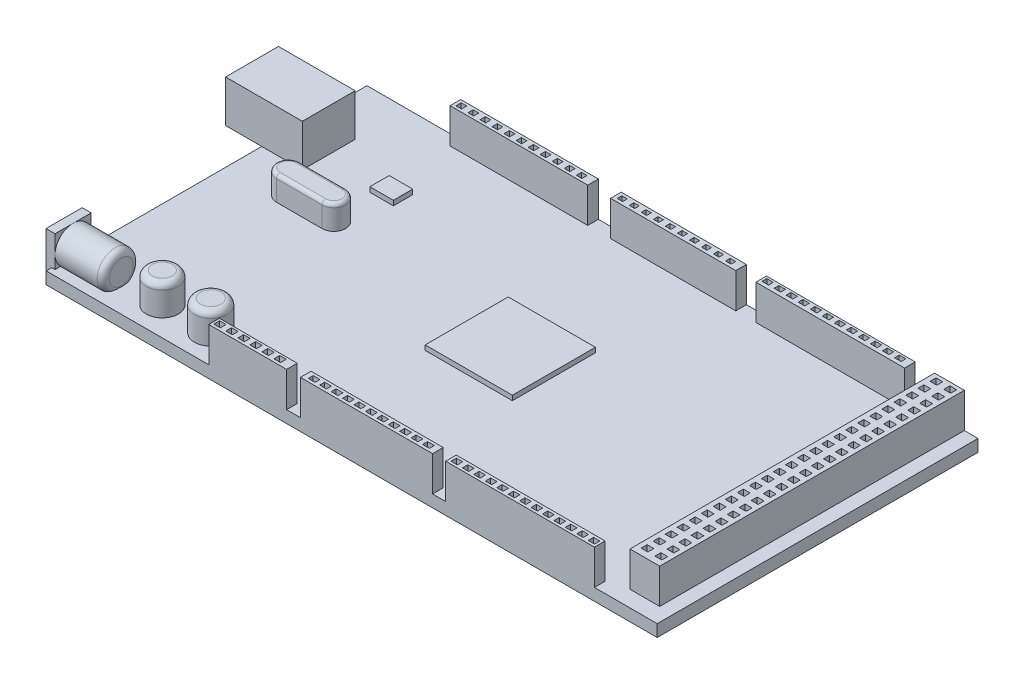
SolidWorks part; units mm, degrees
ref_plane "Front Plane" through (0, 0, 0) normal (0, 0, 1) x (1, 0, 0)
ref_plane "Top Plane" through (0, 0, 0) normal (0, 1, 0) x (1, 0, 0)
ref_plane "Right Plane" through (0, 0, 0) normal (1, 0, 0) x (0, 0, -1)
other "Center of Mass"
sketch "Sketch1" plane through (0, 0, 0) normal (0, 1, 0) x (1, 0, 0)
  line L1 (-53.5463, 29.6807) -> (47.9737, 29.6807)
  line L2 (-53.5463, 29.6807) -> (-53.5463, -23.6193)
  line L3 (-53.5463, -23.6193) -> (47.9737, -23.6193)
  line L4 (47.9737, 29.6807) -> (47.9737, -23.6193)
  dimension "D1" = 101.52
  dimension "D2" = 53.3
extrude "Boss-Extrude1" add sketch "Sketch1" along normal blind 2
sketch "Sketch2" plane through (0, 2, 0) normal (0, 1, 0) x (1, 0, 0)
  line L0 (-53.5463, 29.6807) -> (-53.5463, -23.6193) construction
  line L1 (-53.5463, 20.9714) -> (-46.798, 20.9714)
  line L2 (-53.5463, 20.9714) -> (-53.5463, 12.1907)
  line L3 (-53.5463, 12.1907) -> (-46.798, 12.1907)
  line L4 (-46.798, 20.9714) -> (-46.798, 12.1907)
extrude "Boss-Extrude2" add sketch "Sketch2" along normal blind 7
sketch "Sketch3" plane through (-53.5463, 0, 0) normal (-1, 0, 0) x (0, 0, 1)
  line L1 (-20.9714, 9) -> (-12.1907, 9)
  line L2 (-20.9714, 9) -> (-20.9714, 2)
  line L3 (-20.9714, 2) -> (-12.1907, 2)
  line L4 (-12.1907, 9) -> (-12.1907, 2)
extrude "Boss-Extrude3" add sketch "Sketch3" along normal blind 6
sketch "Sketch4" plane through (-59.5463, 0, 0) normal (-1, 0, 0) x (0, 0, 1)
  line L0 (-16.581, 9) -> (-16.581, 2) construction
  line L1 (-12.1907, 9) -> (-20.9714, 9) construction
  line L2 (-20.9714, 2) -> (-12.1907, 2) construction
  line L3 (-14.3094, 7.9433) -> (-18.8527, 7.9433)
  line L4 (-18.8527, 7.9433) -> (-20.4463, 6.3497)
  line L5 (-20.4463, 6.3497) -> (-20.4463, 2.9918)
  line L6 (-20.4463, 2.9918) -> (-12.7158, 2.9918)
  line L7 (-12.7158, 6.3497) -> (-12.7158, 2.9918)
  line L8 (-14.3094, 7.9433) -> (-12.7158, 6.3497)
  line L10 (-18.8527, 5.6667) -> (-14.3094, 5.6667)
  line L11 (-18.8527, 5.6667) -> (-18.8527, 4.6423)
  line L12 (-18.8527, 4.6423) -> (-14.3094, 4.6423)
  line L13 (-14.3094, 5.6667) -> (-14.3094, 4.6423)
  point P12 (-16.581, 2.9918)
  point P14 (-16.581, 7.9433)
extrude "Cut-Extrude1" cut sketch "Sketch4" against normal blind 10
ref_plane "Plane1" through (-45, 0, 0) normal (1, 0, 0) x (0, 0, -1)
sketch "Sketch5" plane through (-45, 0, 0) normal (1, 0, 0) x (0, 0, -1)
  circle A0 centre (-19.695, 4.1557) radius 3
  dimension "D1" = 6
extrude "Boss-Extrude4" add sketch "Sketch5" against normal blind 8 separate body
fillet "Fillet1" radius 1 1 edges at (-45, 4.1557, 16.695)
sketch "Sketch6" plane through (-53, 0, 0) normal (-1, 0, 0) x (0, 0, 1)
  line L1 (16.695, 1.1557) -> (22.695, 1.1557)
  line L2 (16.695, 1.1557) -> (16.695, 7.1557)
  line L3 (16.695, 7.1557) -> (22.695, 7.1557)
  line L4 (22.695, 1.1557) -> (22.695, 7.1557)
  line L5 (16.695, 1.1557) -> (22.695, 7.1557) construction
  line L6 (16.695, 7.1557) -> (22.695, 1.1557) construction
  point P0 (19.695, 4.1557)
  dimension "D1" = 6
extrude "Boss-Extrude6" add sketch "Sketch6" along normal blind 1.5 separate body
sketch "Sketch8" plane through (-54.5, 0, 0) normal (-1, 0, 0) x (0, 0, 1)
  circle A0 centre (19.695, 4.1557) radius 2.5
  circle A1 centre (19.695, 4.1557) radius 0.3497
  dimension "D1" = 5
extrude "Cut-Extrude5" cut sketch "Sketch8" against normal blind 6
sketch "Sketch9" plane through (0, 2, 0) normal (0, 1, 0) x (1, 0, 0)
  circle A0 centre (-39.0028, -18.8646) radius 2.6535
  circle A1 centre (-30.9573, -18.8646) radius 2.7126
extrude "Boss-Extrude7" add sketch "Sketch9" along normal blind 5
fillet "Fillet2" radius 1 2 edges at (-30.9573, 7, 21.5771) (-39.0028, 7, 21.5181)
sketch "Sketch10" plane through (0, 2, 0) normal (0, 1, 0) x (1, 0, 0)
  line L0 (-44.2898, 7.3408) -> (-36.704, 7.3408) construction
  line L1 (-44.2898, 9.2947) -> (-36.704, 9.2947)
  line L2 (-44.2898, 5.3869) -> (-36.704, 5.3869)
  arc A0 (-44.2898, 9.2947) -> (-44.2898, 5.3869) centre (-44.2898, 7.3408) ccw
  arc A1 (-36.704, 5.3869) -> (-36.704, 9.2947) centre (-36.704, 7.3408) ccw
  point P2 (-40.4969, 7.3408)
extrude "Boss-Extrude8" add sketch "Sketch10" along normal blind 4
fillet "Fillet3" radius 0.6 4 edges at (-46.2437, 6, -7.3408) (-40.4969, 6, -9.2947) (-34.7501, 6, -7.3408) (-40.4969, 6, -5.3869)
sketch "Sketch11" plane through (0, 2, 0) normal (0, 1, 0) x (1, 0, 0)
  line L1 (-10.6137, -3.5781) -> (3.8682, -3.5781)
  line L2 (-10.6137, -3.5781) -> (-10.6137, 10.2142)
  line L3 (-10.6137, 10.2142) -> (3.8682, 10.2142)
  line L4 (3.8682, -3.5781) -> (3.8682, 10.2142)
  line L5 (-10.6137, -3.5781) -> (3.8682, 10.2142) construction
  line L6 (-10.6137, 10.2142) -> (3.8682, -3.5781) construction
  line L7 (-37.9683, 14.5817) -> (-34.0605, 14.5817)
  line L8 (-37.9683, 14.5817) -> (-37.9683, 17.7999)
  line L9 (-37.9683, 17.7999) -> (-34.0605, 17.7999)
  line L10 (-34.0605, 14.5817) -> (-34.0605, 17.7999)
  line L11 (-37.9683, 14.5817) -> (-34.0605, 17.7999) construction
  line L12 (-37.9683, 17.7999) -> (-34.0605, 14.5817) construction
  point P0 (-3.3727, 3.318)
  point P5 (-36.0144, 16.1908)
extrude "Boss-Extrude9" add sketch "Sketch11" along normal blind 0.8
sketch "Sketch12" plane through (0, 2, 0) normal (0, 1, 0) x (1, 0, 0)
  line L0 (47.9737, 29.6807) -> (-53.5463, 29.6807) construction
  line L1 (-37.9683, 29.6807) -> (-15.0961, 29.6807)
  line L2 (-37.9683, 29.6807) -> (-37.9683, 27.9107)
  line L3 (-37.9683, 27.9107) -> (-15.0961, 27.9107)
  line L4 (-15.0961, 29.6807) -> (-15.0961, 27.9107)
  line L5 (-53.5463, -23.6193) -> (47.9737, -23.6193) construction
  line L6 (-11.3033, 29.6807) -> (9.5001, 29.6807)
  line L7 (-11.3033, 29.6807) -> (-11.3033, 27.9107)
  line L8 (-11.3033, 27.9107) -> (9.5001, 27.9107)
  line L9 (9.5001, 29.6807) -> (9.5001, 27.9107)
  line L10 (12.8332, 29.6807) -> (37.5444, 29.6807)
  line L11 (12.8332, 29.6807) -> (12.8332, 27.9107)
  line L12 (12.8332, 27.9107) -> (37.5444, 27.9107)
  line L13 (37.5444, 29.6807) -> (37.5444, 27.9107)
  line L14 (40.7626, 29.6807) -> (45.7048, 29.6807)
  line L15 (40.7626, 29.6807) -> (40.7626, -20.9334)
  line L16 (40.7626, -20.9334) -> (45.7048, -20.9334)
  line L17 (45.7048, 29.6807) -> (45.7048, -20.9334)
  line L18 (37.5444, -23.6193) -> (12.8332, -23.6193)
  line L19 (37.5444, -23.6193) -> (37.5444, -21.8493)
  line L20 (37.5444, -21.8493) -> (12.8332, -21.8493)
  line L21 (12.8332, -23.6193) -> (12.8332, -21.8493)
  line L23 (10.6494, -23.6193) -> (-11.3033, -23.6193)
  line L24 (10.6494, -23.6193) -> (10.6494, -21.8493)
  line L25 (10.6494, -21.8493) -> (-11.3033, -21.8493)
  line L26 (-11.3033, -23.6193) -> (-11.3033, -21.8493)
  line L27 (-13.602, -23.6193) -> (-26.5322, -23.6193)
  line L28 (-13.602, -23.6193) -> (-13.602, -21.8493)
  line L29 (-13.602, -21.8493) -> (-26.5322, -21.8493)
  line L30 (-26.5322, -23.6193) -> (-26.5322, -21.8493)
  dimension "D1" = 1.77
  dimension "D2" = 1.77
  dimension "D3" = 1.77
  dimension "D4" = 1.77
  dimension "D5" = 1.77
  dimension "D6" = 1.77
extrude "Boss-Extrude10" add sketch "Sketch12" along normal blind 5.8
sketch "Sketch13" plane through (0, 7.8, 0) normal (0, 1, 0) x (1, 0, 0)
  line L0 (-35.4587, 29.2432) -> (-35.4587, 28.3704)
  line L1 (-37.4587, 29.2432) -> (-36.5314, 29.2432)
  line L2 (-37.4587, 29.2432) -> (-37.4587, 28.3704)
  line L3 (-37.4587, 28.3704) -> (-36.5314, 28.3704)
  line L4 (-36.5314, 29.2432) -> (-36.5314, 28.3704)
  line L5 (-35.4587, 29.2432) -> (-34.5314, 29.2432)
  line L6 (-34.5314, 29.2432) -> (-34.5314, 28.3704)
  line L7 (-35.4587, 28.3704) -> (-34.5314, 28.3704)
  line L8 (-33.4587, 29.2432) -> (-33.4587, 28.3704)
  line L9 (-33.4587, 29.2432) -> (-32.5314, 29.2432)
  line L10 (-32.5314, 29.2432) -> (-32.5314, 28.3704)
  line L11 (-33.4587, 28.3704) -> (-32.5314, 28.3704)
  line L12 (-31.4587, 29.2432) -> (-31.4587, 28.3704)
  line L13 (-31.4587, 29.2432) -> (-30.5314, 29.2432)
  line L14 (-30.5314, 29.2432) -> (-30.5314, 28.3704)
  line L15 (-31.4587, 28.3704) -> (-30.5314, 28.3704)
  line L16 (-29.4587, 29.2432) -> (-29.4587, 28.3704)
  line L17 (-29.4587, 29.2432) -> (-28.5314, 29.2432)
  line L18 (-28.5314, 29.2432) -> (-28.5314, 28.3704)
  line L19 (-29.4587, 28.3704) -> (-28.5314, 28.3704)
  line L20 (-27.4587, 29.2432) -> (-27.4587, 28.3704)
  line L21 (-27.4587, 29.2432) -> (-26.5314, 29.2432)
  line L22 (-26.5314, 29.2432) -> (-26.5314, 28.3704)
  line L23 (-27.4587, 28.3704) -> (-26.5314, 28.3704)
  line L24 (-25.4587, 29.2432) -> (-25.4587, 28.3704)
  line L25 (-25.4587, 29.2432) -> (-24.5314, 29.2432)
  line L26 (-24.5314, 29.2432) -> (-24.5314, 28.3704)
  line L27 (-25.4587, 28.3704) -> (-24.5314, 28.3704)
  line L28 (-23.4587, 29.2432) -> (-23.4587, 28.3704)
  line L29 (-23.4587, 29.2432) -> (-22.5314, 29.2432)
  line L30 (-22.5314, 29.2432) -> (-22.5314, 28.3704)
  line L31 (-23.4587, 28.3704) -> (-22.5314, 28.3704)
  line L32 (-21.4587, 29.2432) -> (-21.4587, 28.3704)
  line L33 (-21.4587, 29.2432) -> (-20.5314, 29.2432)
  line L34 (-20.5314, 29.2432) -> (-20.5314, 28.3704)
  line L35 (-21.4587, 28.3704) -> (-20.5314, 28.3704)
  line L36 (-19.4587, 29.2432) -> (-19.4587, 28.3704)
  line L37 (-19.4587, 29.2432) -> (-18.5314, 29.2432)
  line L38 (-18.5314, 29.2432) -> (-18.5314, 28.3704)
  line L39 (-19.4587, 28.3704) -> (-18.5314, 28.3704)
  line L40 (-17.4587, 29.2432) -> (-17.4587, 28.3704)
  line L41 (-17.4587, 29.2432) -> (-16.5314, 29.2432)
  line L42 (-16.5314, 29.2432) -> (-16.5314, 28.3704)
  line L43 (-17.4587, 28.3704) -> (-16.5314, 28.3704)
  dimension "D1" = 11
extrude "Cut-Extrude6" cut sketch "Sketch13" against normal blind 4.8
sketch "Sketch14" plane through (0, 7.8, 0) normal (0, 1, 0) x (1, 0, 0)
  line L0 (-8.7327, 29.2151) -> (-8.7327, 28.4454)
  line L1 (-10.7327, 29.2151) -> (-9.8272, 29.2151)
  line L2 (-10.7327, 29.2151) -> (-10.7327, 28.4454)
  line L3 (-10.7327, 28.4454) -> (-9.8272, 28.4454)
  line L4 (-9.8272, 29.2151) -> (-9.8272, 28.4454)
  line L5 (-8.7327, 29.2151) -> (-7.8272, 29.2151)
  line L6 (-7.8272, 29.2151) -> (-7.8272, 28.4454)
  line L7 (-8.7327, 28.4454) -> (-7.8272, 28.4454)
  line L8 (-6.7327, 29.2151) -> (-6.7327, 28.4454)
  line L9 (-6.7327, 29.2151) -> (-5.8272, 29.2151)
  line L10 (-5.8272, 29.2151) -> (-5.8272, 28.4454)
  line L11 (-6.7327, 28.4454) -> (-5.8272, 28.4454)
  line L12 (-4.7327, 29.2151) -> (-4.7327, 28.4454)
  line L13 (-4.7327, 29.2151) -> (-3.8272, 29.2151)
  line L14 (-3.8272, 29.2151) -> (-3.8272, 28.4454)
  line L15 (-4.7327, 28.4454) -> (-3.8272, 28.4454)
  line L16 (-2.7327, 29.2151) -> (-2.7327, 28.4454)
  line L17 (-2.7327, 29.2151) -> (-1.8272, 29.2151)
  line L18 (-1.8272, 29.2151) -> (-1.8272, 28.4454)
  line L19 (-2.7327, 28.4454) -> (-1.8272, 28.4454)
  line L20 (-0.7327, 29.2151) -> (-0.7327, 28.4454)
  line L21 (-0.7327, 29.2151) -> (0.1728, 29.2151)
  line L22 (0.1728, 29.2151) -> (0.1728, 28.4454)
  line L23 (-0.7327, 28.4454) -> (0.1728, 28.4454)
  line L24 (1.2673, 29.2151) -> (1.2673, 28.4454)
  line L25 (1.2673, 29.2151) -> (2.1728, 29.2151)
  line L26 (2.1728, 29.2151) -> (2.1728, 28.4454)
  line L27 (1.2673, 28.4454) -> (2.1728, 28.4454)
  line L28 (3.2673, 29.2151) -> (3.2673, 28.4454)
  line L29 (3.2673, 29.2151) -> (4.1728, 29.2151)
  line L30 (4.1728, 29.2151) -> (4.1728, 28.4454)
  line L31 (3.2673, 28.4454) -> (4.1728, 28.4454)
  line L32 (5.2673, 29.2151) -> (5.2673, 28.4454)
  line L33 (5.2673, 29.2151) -> (6.1728, 29.2151)
  line L34 (6.1728, 29.2151) -> (6.1728, 28.4454)
  line L35 (5.2673, 28.4454) -> (6.1728, 28.4454)
  line L36 (7.2673, 29.2151) -> (7.2673, 28.4454)
  line L37 (7.2673, 29.2151) -> (8.1728, 29.2151)
  line L38 (8.1728, 29.2151) -> (8.1728, 28.4454)
  line L39 (7.2673, 28.4454) -> (8.1728, 28.4454)
  dimension "D1" = 10
extrude "Cut-Extrude7" cut sketch "Sketch14" against normal blind 3.8
sketch "Sketch15" plane through (0, 7.8, 0) normal (0, 1, 0) x (1, 0, 0)
  line L0 (15.2291, 29.3382) -> (15.2291, 28.5491)
  line L1 (13.2291, 29.3382) -> (14.3188, 29.3382)
  line L2 (13.2291, 29.3382) -> (13.2291, 28.5491)
  line L3 (13.2291, 28.5491) -> (14.3188, 28.5491)
  line L4 (14.3188, 29.3382) -> (14.3188, 28.5491)
  line L5 (15.2291, 29.3382) -> (16.3188, 29.3382)
  line L6 (16.3188, 29.3382) -> (16.3188, 28.5491)
  line L7 (15.2291, 28.5491) -> (16.3188, 28.5491)
  line L8 (17.2291, 29.3382) -> (17.2291, 28.5491)
  line L9 (17.2291, 29.3382) -> (18.3188, 29.3382)
  line L10 (18.3188, 29.3382) -> (18.3188, 28.5491)
  line L11 (17.2291, 28.5491) -> (18.3188, 28.5491)
  line L12 (19.2291, 29.3382) -> (19.2291, 28.5491)
  line L13 (19.2291, 29.3382) -> (20.3188, 29.3382)
  line L14 (20.3188, 29.3382) -> (20.3188, 28.5491)
  line L15 (19.2291, 28.5491) -> (20.3188, 28.5491)
  line L16 (21.2291, 29.3382) -> (21.2291, 28.5491)
  line L17 (21.2291, 29.3382) -> (22.3188, 29.3382)
  line L18 (22.3188, 29.3382) -> (22.3188, 28.5491)
  line L19 (21.2291, 28.5491) -> (22.3188, 28.5491)
  line L20 (23.2291, 29.3382) -> (23.2291, 28.5491)
  line L21 (23.2291, 29.3382) -> (24.3188, 29.3382)
  line L22 (24.3188, 29.3382) -> (24.3188, 28.5491)
  line L23 (23.2291, 28.5491) -> (24.3188, 28.5491)
  line L24 (25.2291, 29.3382) -> (25.2291, 28.5491)
  line L25 (25.2291, 29.3382) -> (26.3188, 29.3382)
  line L26 (26.3188, 29.3382) -> (26.3188, 28.5491)
  line L27 (25.2291, 28.5491) -> (26.3188, 28.5491)
  line L28 (27.2291, 29.3382) -> (27.2291, 28.5491)
  line L29 (27.2291, 29.3382) -> (28.3188, 29.3382)
  line L30 (28.3188, 29.3382) -> (28.3188, 28.5491)
  line L31 (27.2291, 28.5491) -> (28.3188, 28.5491)
  line L32 (29.2291, 29.3382) -> (29.2291, 28.5491)
  line L33 (29.2291, 29.3382) -> (30.3188, 29.3382)
  line L34 (30.3188, 29.3382) -> (30.3188, 28.5491)
  line L35 (29.2291, 28.5491) -> (30.3188, 28.5491)
  line L36 (31.2291, 29.3382) -> (31.2291, 28.5491)
  line L37 (31.2291, 29.3382) -> (32.3188, 29.3382)
  line L38 (32.3188, 29.3382) -> (32.3188, 28.5491)
  line L39 (31.2291, 28.5491) -> (32.3188, 28.5491)
  line L40 (33.2291, 29.3382) -> (33.2291, 28.5491)
  line L41 (33.2291, 29.3382) -> (34.3188, 29.3382)
  line L42 (34.3188, 29.3382) -> (34.3188, 28.5491)
  line L43 (33.2291, 28.5491) -> (34.3188, 28.5491)
  line L44 (35.2291, 29.3382) -> (35.2291, 28.5491)
  line L45 (35.2291, 29.3382) -> (36.3188, 29.3382)
  line L46 (36.3188, 29.3382) -> (36.3188, 28.5491)
  line L47 (35.2291, 28.5491) -> (36.3188, 28.5491)
  dimension "D1" = 12
extrude "Cut-Extrude8" cut sketch "Sketch15" against normal blind 3.8
sketch "Sketch17" plane through (0, 7.8, 0) normal (0, 1, 0) x (1, 0, 0)
  line L0 (-24.1716, -22.1907) -> (-24.1716, -23.1485)
  line L1 (-26.1716, -22.1907) -> (-25.0843, -22.1907)
  line L2 (-26.1716, -22.1907) -> (-26.1716, -23.1485)
  line L3 (-26.1716, -23.1485) -> (-25.0843, -23.1485)
  line L4 (-25.0843, -22.1907) -> (-25.0843, -23.1485)
  line L5 (-24.1716, -22.1907) -> (-23.0843, -22.1907)
  line L6 (-23.0843, -22.1907) -> (-23.0843, -23.1485)
  line L7 (-24.1716, -23.1485) -> (-23.0843, -23.1485)
  line L8 (-22.1716, -22.1907) -> (-22.1716, -23.1485)
  line L9 (-22.1716, -22.1907) -> (-21.0843, -22.1907)
  line L10 (-21.0843, -22.1907) -> (-21.0843, -23.1485)
  line L11 (-22.1716, -23.1485) -> (-21.0843, -23.1485)
  line L12 (-20.1716, -22.1907) -> (-20.1716, -23.1485)
  line L13 (-20.1716, -22.1907) -> (-19.0843, -22.1907)
  line L14 (-19.0843, -22.1907) -> (-19.0843, -23.1485)
  line L15 (-20.1716, -23.1485) -> (-19.0843, -23.1485)
  line L16 (-18.1716, -22.1907) -> (-18.1716, -23.1485)
  line L17 (-18.1716, -22.1907) -> (-17.0843, -22.1907)
  line L18 (-17.0843, -22.1907) -> (-17.0843, -23.1485)
  line L19 (-18.1716, -23.1485) -> (-17.0843, -23.1485)
  line L20 (-16.1716, -22.1907) -> (-16.1716, -23.1485)
  line L21 (-16.1716, -22.1907) -> (-15.0843, -22.1907)
  line L22 (-15.0843, -22.1907) -> (-15.0843, -23.1485)
  line L23 (-16.1716, -23.1485) -> (-15.0843, -23.1485)
  dimension "D1" = 6
extrude "Cut-Extrude9" cut sketch "Sketch17" against normal blind 3.8
sketch "Sketch18" plane through (0, 7.8, 0) normal (0, 1, 0) x (1, 0, 0)
  line L0 (-8.5998, -22.2974) -> (-8.5998, -23.1241)
  line L1 (-10.4998, -22.2974) -> (-9.3725, -22.2974)
  line L2 (-10.4998, -22.2974) -> (-10.4998, -23.1241)
  line L3 (-10.4998, -23.1241) -> (-9.3725, -23.1241)
  line L4 (-9.3725, -22.2974) -> (-9.3725, -23.1241)
  line L5 (-8.5998, -22.2974) -> (-7.4725, -22.2974)
  line L6 (-7.4725, -22.2974) -> (-7.4725, -23.1241)
  line L7 (-8.5998, -23.1241) -> (-7.4725, -23.1241)
  line L8 (-6.6998, -22.2974) -> (-6.6998, -23.1241)
  line L9 (-6.6998, -22.2974) -> (-5.5725, -22.2974)
  line L10 (-5.5725, -22.2974) -> (-5.5725, -23.1241)
  line L11 (-6.6998, -23.1241) -> (-5.5725, -23.1241)
  line L12 (-4.7998, -22.2974) -> (-4.7998, -23.1241)
  line L13 (-4.7998, -22.2974) -> (-3.6725, -22.2974)
  line L14 (-3.6725, -22.2974) -> (-3.6725, -23.1241)
  line L15 (-4.7998, -23.1241) -> (-3.6725, -23.1241)
  line L16 (-2.8998, -22.2974) -> (-2.8998, -23.1241)
  line L17 (-2.8998, -22.2974) -> (-1.7725, -22.2974)
  line L18 (-1.7725, -22.2974) -> (-1.7725, -23.1241)
  line L19 (-2.8998, -23.1241) -> (-1.7725, -23.1241)
  line L20 (-0.9998, -22.2974) -> (-0.9998, -23.1241)
  line L21 (-0.9998, -22.2974) -> (0.1275, -22.2974)
  line L22 (0.1275, -22.2974) -> (0.1275, -23.1241)
  line L23 (-0.9998, -23.1241) -> (0.1275, -23.1241)
  line L24 (0.9002, -22.2974) -> (0.9002, -23.1241)
  line L25 (0.9002, -22.2974) -> (2.0275, -22.2974)
  line L26 (2.0275, -22.2974) -> (2.0275, -23.1241)
  line L27 (0.9002, -23.1241) -> (2.0275, -23.1241)
  line L28 (2.8002, -22.2974) -> (2.8002, -23.1241)
  line L29 (2.8002, -22.2974) -> (3.9275, -22.2974)
  line L30 (3.9275, -22.2974) -> (3.9275, -23.1241)
  line L31 (2.8002, -23.1241) -> (3.9275, -23.1241)
  line L32 (4.7002, -22.2974) -> (4.7002, -23.1241)
  line L33 (4.7002, -22.2974) -> (5.8275, -22.2974)
  line L34 (5.8275, -22.2974) -> (5.8275, -23.1241)
  line L35 (4.7002, -23.1241) -> (5.8275, -23.1241)
  line L36 (6.6002, -22.2974) -> (6.6002, -23.1241)
  line L37 (6.6002, -22.2974) -> (7.7275, -22.2974)
  line L38 (7.7275, -22.2974) -> (7.7275, -23.1241)
  line L39 (6.6002, -23.1241) -> (7.7275, -23.1241)
  line L40 (8.5002, -22.2974) -> (8.5002, -23.1241)
  line L41 (8.5002, -22.2974) -> (9.6275, -22.2974)
  line L42 (9.6275, -22.2974) -> (9.6275, -23.1241)
  line L43 (8.5002, -23.1241) -> (9.6275, -23.1241)
  dimension "D1" = 11
extrude "Cut-Extrude10" cut sketch "Sketch18" against normal blind 3.8
sketch "Sketch19" plane through (0, 7.8, 0) normal (0, 1, 0) x (1, 0, 0)
  line L0 (15.1727, -22.2847) -> (15.1727, -23.1784)
  line L1 (13.2727, -22.2847) -> (14.3205, -22.2847)
  line L2 (13.2727, -22.2847) -> (13.2727, -23.1784)
  line L3 (13.2727, -23.1784) -> (14.3205, -23.1784)
  line L4 (14.3205, -22.2847) -> (14.3205, -23.1784)
  line L5 (15.1727, -22.2847) -> (16.2205, -22.2847)
  line L6 (16.2205, -22.2847) -> (16.2205, -23.1784)
  line L7 (15.1727, -23.1784) -> (16.2205, -23.1784)
  line L8 (17.0727, -22.2847) -> (17.0727, -23.1784)
  line L9 (17.0727, -22.2847) -> (18.1205, -22.2847)
  line L10 (18.1205, -22.2847) -> (18.1205, -23.1784)
  line L11 (17.0727, -23.1784) -> (18.1205, -23.1784)
  line L12 (18.9727, -22.2847) -> (18.9727, -23.1784)
  line L13 (18.9727, -22.2847) -> (20.0205, -22.2847)
  line L14 (20.0205, -22.2847) -> (20.0205, -23.1784)
  line L15 (18.9727, -23.1784) -> (20.0205, -23.1784)
  line L16 (20.8727, -22.2847) -> (20.8727, -23.1784)
  line L17 (20.8727, -22.2847) -> (21.9205, -22.2847)
  line L18 (21.9205, -22.2847) -> (21.9205, -23.1784)
  line L19 (20.8727, -23.1784) -> (21.9205, -23.1784)
  line L20 (22.7727, -22.2847) -> (22.7727, -23.1784)
  line L21 (22.7727, -22.2847) -> (23.8205, -22.2847)
  line L22 (23.8205, -22.2847) -> (23.8205, -23.1784)
  line L23 (22.7727, -23.1784) -> (23.8205, -23.1784)
  line L24 (24.6727, -22.2847) -> (24.6727, -23.1784)
  line L25 (24.6727, -22.2847) -> (25.7205, -22.2847)
  line L26 (25.7205, -22.2847) -> (25.7205, -23.1784)
  line L27 (24.6727, -23.1784) -> (25.7205, -23.1784)
  line L28 (26.5727, -22.2847) -> (26.5727, -23.1784)
  line L29 (26.5727, -22.2847) -> (27.6205, -22.2847)
  line L30 (27.6205, -22.2847) -> (27.6205, -23.1784)
  line L31 (26.5727, -23.1784) -> (27.6205, -23.1784)
  line L32 (28.4727, -22.2847) -> (28.4727, -23.1784)
  line L33 (28.4727, -22.2847) -> (29.5205, -22.2847)
  line L34 (29.5205, -22.2847) -> (29.5205, -23.1784)
  line L35 (28.4727, -23.1784) -> (29.5205, -23.1784)
  line L36 (30.3727, -22.2847) -> (30.3727, -23.1784)
  line L37 (30.3727, -22.2847) -> (31.4205, -22.2847)
  line L38 (31.4205, -22.2847) -> (31.4205, -23.1784)
  line L39 (30.3727, -23.1784) -> (31.4205, -23.1784)
  line L40 (32.2727, -22.2847) -> (32.2727, -23.1784)
  line L41 (32.2727, -22.2847) -> (33.3205, -22.2847)
  line L42 (33.3205, -22.2847) -> (33.3205, -23.1784)
  line L43 (32.2727, -23.1784) -> (33.3205, -23.1784)
  line L44 (34.1727, -22.2847) -> (34.1727, -23.1784)
  line L45 (34.1727, -22.2847) -> (35.2205, -22.2847)
  line L46 (35.2205, -22.2847) -> (35.2205, -23.1784)
  line L47 (34.1727, -23.1784) -> (35.2205, -23.1784)
  line L48 (36.0727, -22.2847) -> (36.0727, -23.1784)
  line L49 (36.0727, -22.2847) -> (37.1205, -22.2847)
  line L50 (37.1205, -22.2847) -> (37.1205, -23.1784)
  line L51 (36.0727, -23.1784) -> (37.1205, -23.1784)
  dimension "D1" = 13
extrude "Cut-Extrude11" cut sketch "Sketch19" against normal blind 3.8
sketch "Sketch20" plane through (0, 7.8, 0) normal (0, 1, 0) x (1, 0, 0)
  line L0 (43.8618, 28.1143) -> (44.9937, 28.1143)
  line L1 (41.5618, 29.1103) -> (42.6937, 29.1103)
  line L2 (41.5618, 29.1103) -> (41.5618, 28.1143)
  line L3 (41.5618, 28.1143) -> (42.6937, 28.1143)
  line L4 (42.6937, 29.1103) -> (42.6937, 28.1143)
  line L5 (44.9937, 29.1103) -> (44.9937, 28.1143)
  line L6 (43.8618, 29.1103) -> (44.9937, 29.1103)
  line L7 (43.8618, 29.1103) -> (43.8618, 28.1143)
  line L8 (43.8618, 26.1143) -> (44.9937, 26.1143)
  line L9 (44.9937, 27.1103) -> (44.9937, 26.1143)
  line L10 (43.8618, 27.1103) -> (44.9937, 27.1103)
  line L11 (43.8618, 27.1103) -> (43.8618, 26.1143)
  line L12 (43.8618, 24.1143) -> (44.9937, 24.1143)
  line L13 (44.9937, 25.1103) -> (44.9937, 24.1143)
  line L14 (43.8618, 25.1103) -> (44.9937, 25.1103)
  line L15 (43.8618, 25.1103) -> (43.8618, 24.1143)
  line L16 (43.8618, 22.1143) -> (44.9937, 22.1143)
  line L17 (44.9937, 23.1103) -> (44.9937, 22.1143)
  line L18 (43.8618, 23.1103) -> (44.9937, 23.1103)
  line L19 (43.8618, 23.1103) -> (43.8618, 22.1143)
  line L20 (43.8618, 20.1143) -> (44.9937, 20.1143)
  line L21 (44.9937, 21.1103) -> (44.9937, 20.1143)
  line L22 (43.8618, 21.1103) -> (44.9937, 21.1103)
  line L23 (43.8618, 21.1103) -> (43.8618, 20.1143)
  line L24 (43.8618, 18.1143) -> (44.9937, 18.1143)
  line L25 (44.9937, 19.1103) -> (44.9937, 18.1143)
  line L26 (43.8618, 19.1103) -> (44.9937, 19.1103)
  line L27 (43.8618, 19.1103) -> (43.8618, 18.1143)
  line L28 (43.8618, 16.1143) -> (44.9937, 16.1143)
  line L29 (44.9937, 17.1103) -> (44.9937, 16.1143)
  line L30 (43.8618, 17.1103) -> (44.9937, 17.1103)
  line L31 (43.8618, 17.1103) -> (43.8618, 16.1143)
  line L32 (43.8618, 14.1143) -> (44.9937, 14.1143)
  line L33 (44.9937, 15.1103) -> (44.9937, 14.1143)
  line L34 (43.8618, 15.1103) -> (44.9937, 15.1103)
  line L35 (43.8618, 15.1103) -> (43.8618, 14.1143)
  line L36 (43.8618, 12.1143) -> (44.9937, 12.1143)
  line L37 (44.9937, 13.1103) -> (44.9937, 12.1143)
  line L38 (43.8618, 13.1103) -> (44.9937, 13.1103)
  line L39 (43.8618, 13.1103) -> (43.8618, 12.1143)
  line L40 (43.8618, 10.1143) -> (44.9937, 10.1143)
  line L41 (44.9937, 11.1103) -> (44.9937, 10.1143)
  line L42 (43.8618, 11.1103) -> (44.9937, 11.1103)
  line L43 (43.8618, 11.1103) -> (43.8618, 10.1143)
  line L44 (43.8618, 8.1143) -> (44.9937, 8.1143)
  line L45 (44.9937, 9.1103) -> (44.9937, 8.1143)
  line L46 (43.8618, 9.1103) -> (44.9937, 9.1103)
  line L47 (43.8618, 9.1103) -> (43.8618, 8.1143)
  line L48 (43.8618, 6.1143) -> (44.9937, 6.1143)
  line L49 (44.9937, 7.1103) -> (44.9937, 6.1143)
  line L50 (43.8618, 7.1103) -> (44.9937, 7.1103)
  line L51 (43.8618, 7.1103) -> (43.8618, 6.1143)
  line L52 (43.8618, 4.1143) -> (44.9937, 4.1143)
  line L53 (44.9937, 5.1103) -> (44.9937, 4.1143)
  line L54 (43.8618, 5.1103) -> (44.9937, 5.1103)
  line L55 (43.8618, 5.1103) -> (43.8618, 4.1143)
  line L56 (43.8618, 2.1143) -> (44.9937, 2.1143)
  line L57 (44.9937, 3.1103) -> (44.9937, 2.1143)
  line L58 (43.8618, 3.1103) -> (44.9937, 3.1103)
  line L59 (43.8618, 3.1103) -> (43.8618, 2.1143)
  line L60 (43.8618, 0.1143) -> (44.9937, 0.1143)
  line L61 (44.9937, 1.1103) -> (44.9937, 0.1143)
  line L62 (43.8618, 1.1103) -> (44.9937, 1.1103)
  line L63 (43.8618, 1.1103) -> (43.8618, 0.1143)
  line L64 (43.8618, -1.8857) -> (44.9937, -1.8857)
  line L65 (44.9937, -0.8897) -> (44.9937, -1.8857)
  line L66 (43.8618, -0.8897) -> (44.9937, -0.8897)
  line L67 (43.8618, -0.8897) -> (43.8618, -1.8857)
  line L68 (43.8618, -3.8857) -> (44.9937, -3.8857)
  line L69 (44.9937, -2.8897) -> (44.9937, -3.8857)
  line L70 (43.8618, -2.8897) -> (44.9937, -2.8897)
  line L71 (43.8618, -2.8897) -> (43.8618, -3.8857)
  line L72 (43.8618, -5.8857) -> (44.9937, -5.8857)
  line L73 (44.9937, -4.8897) -> (44.9937, -5.8857)
  line L74 (43.8618, -4.8897) -> (44.9937, -4.8897)
  line L75 (43.8618, -4.8897) -> (43.8618, -5.8857)
  line L76 (43.8618, -7.8857) -> (44.9937, -7.8857)
  line L77 (44.9937, -6.8897) -> (44.9937, -7.8857)
  line L78 (43.8618, -6.8897) -> (44.9937, -6.8897)
  line L79 (43.8618, -6.8897) -> (43.8618, -7.8857)
  line L80 (43.8618, -9.8857) -> (44.9937, -9.8857)
  line L81 (44.9937, -8.8897) -> (44.9937, -9.8857)
  line L82 (43.8618, -8.8897) -> (44.9937, -8.8897)
  line L83 (43.8618, -8.8897) -> (43.8618, -9.8857)
  line L84 (43.8618, -11.8857) -> (44.9937, -11.8857)
  line L85 (44.9937, -10.8897) -> (44.9937, -11.8857)
  line L86 (43.8618, -10.8897) -> (44.9937, -10.8897)
  line L87 (43.8618, -10.8897) -> (43.8618, -11.8857)
  line L88 (43.8618, -13.8857) -> (44.9937, -13.8857)
  line L89 (44.9937, -12.8897) -> (44.9937, -13.8857)
  line L90 (43.8618, -12.8897) -> (44.9937, -12.8897)
  line L91 (43.8618, -12.8897) -> (43.8618, -13.8857)
  line L92 (43.8618, -15.8857) -> (44.9937, -15.8857)
  line L93 (44.9937, -14.8897) -> (44.9937, -15.8857)
  line L94 (43.8618, -14.8897) -> (44.9937, -14.8897)
  line L95 (43.8618, -14.8897) -> (43.8618, -15.8857)
  line L96 (43.8618, -17.8857) -> (44.9937, -17.8857)
  line L97 (44.9937, -16.8897) -> (44.9937, -17.8857)
  line L98 (43.8618, -16.8897) -> (44.9937, -16.8897)
  line L99 (43.8618, -16.8897) -> (43.8618, -17.8857)
  line L100 (43.8618, -19.8857) -> (44.9937, -19.8857)
  line L101 (44.9937, -18.8897) -> (44.9937, -19.8857)
  line L102 (43.8618, -18.8897) -> (44.9937, -18.8897)
  line L103 (43.8618, -18.8897) -> (43.8618, -19.8857)
  line L104 (41.5618, 26.1143) -> (42.6937, 26.1143)
  line L105 (42.6937, 27.1103) -> (42.6937, 26.1143)
  line L106 (41.5618, 27.1103) -> (42.6937, 27.1103)
  line L107 (41.5618, 27.1103) -> (41.5618, 26.1143)
  line L108 (41.5618, 24.1143) -> (42.6937, 24.1143)
  line L109 (42.6937, 25.1103) -> (42.6937, 24.1143)
  line L110 (41.5618, 25.1103) -> (42.6937, 25.1103)
  line L111 (41.5618, 25.1103) -> (41.5618, 24.1143)
  line L112 (41.5618, 22.1143) -> (42.6937, 22.1143)
  line L113 (42.6937, 23.1103) -> (42.6937, 22.1143)
  line L114 (41.5618, 23.1103) -> (42.6937, 23.1103)
  line L115 (41.5618, 23.1103) -> (41.5618, 22.1143)
  line L116 (41.5618, 20.1143) -> (42.6937, 20.1143)
  line L117 (42.6937, 21.1103) -> (42.6937, 20.1143)
  line L118 (41.5618, 21.1103) -> (42.6937, 21.1103)
  line L119 (41.5618, 21.1103) -> (41.5618, 20.1143)
  line L120 (41.5618, 18.1143) -> (42.6937, 18.1143)
  line L121 (42.6937, 19.1103) -> (42.6937, 18.1143)
  line L122 (41.5618, 19.1103) -> (42.6937, 19.1103)
  line L123 (41.5618, 19.1103) -> (41.5618, 18.1143)
  line L124 (41.5618, 16.1143) -> (42.6937, 16.1143)
  line L125 (42.6937, 17.1103) -> (42.6937, 16.1143)
  line L126 (41.5618, 17.1103) -> (42.6937, 17.1103)
  line L127 (41.5618, 17.1103) -> (41.5618, 16.1143)
  line L128 (41.5618, 14.1143) -> (42.6937, 14.1143)
  line L129 (42.6937, 15.1103) -> (42.6937, 14.1143)
  line L130 (41.5618, 15.1103) -> (42.6937, 15.1103)
  line L131 (41.5618, 15.1103) -> (41.5618, 14.1143)
  line L132 (41.5618, 12.1143) -> (42.6937, 12.1143)
  line L133 (42.6937, 13.1103) -> (42.6937, 12.1143)
  line L134 (41.5618, 13.1103) -> (42.6937, 13.1103)
  line L135 (41.5618, 13.1103) -> (41.5618, 12.1143)
  line L136 (41.5618, 10.1143) -> (42.6937, 10.1143)
  line L137 (42.6937, 11.1103) -> (42.6937, 10.1143)
  line L138 (41.5618, 11.1103) -> (42.6937, 11.1103)
  line L139 (41.5618, 11.1103) -> (41.5618, 10.1143)
  line L140 (41.5618, 8.1143) -> (42.6937, 8.1143)
  line L141 (42.6937, 9.1103) -> (42.6937, 8.1143)
  line L142 (41.5618, 9.1103) -> (42.6937, 9.1103)
  line L143 (41.5618, 9.1103) -> (41.5618, 8.1143)
  line L144 (41.5618, 6.1143) -> (42.6937, 6.1143)
  line L145 (42.6937, 7.1103) -> (42.6937, 6.1143)
  line L146 (41.5618, 7.1103) -> (42.6937, 7.1103)
  line L147 (41.5618, 7.1103) -> (41.5618, 6.1143)
  line L148 (41.5618, 4.1143) -> (42.6937, 4.1143)
  line L149 (42.6937, 5.1103) -> (42.6937, 4.1143)
  line L150 (41.5618, 5.1103) -> (42.6937, 5.1103)
  line L151 (41.5618, 5.1103) -> (41.5618, 4.1143)
  line L152 (41.5618, 2.1143) -> (42.6937, 2.1143)
  line L153 (42.6937, 3.1103) -> (42.6937, 2.1143)
  line L154 (41.5618, 3.1103) -> (42.6937, 3.1103)
  line L155 (41.5618, 3.1103) -> (41.5618, 2.1143)
  line L156 (41.5618, 0.1143) -> (42.6937, 0.1143)
  line L157 (42.6937, 1.1103) -> (42.6937, 0.1143)
  line L158 (41.5618, 1.1103) -> (42.6937, 1.1103)
  line L159 (41.5618, 1.1103) -> (41.5618, 0.1143)
  line L160 (41.5618, -1.8857) -> (42.6937, -1.8857)
  line L161 (42.6937, -0.8897) -> (42.6937, -1.8857)
  line L162 (41.5618, -0.8897) -> (42.6937, -0.8897)
  line L163 (41.5618, -0.8897) -> (41.5618, -1.8857)
  line L164 (41.5618, -3.8857) -> (42.6937, -3.8857)
  line L165 (42.6937, -2.8897) -> (42.6937, -3.8857)
  line L166 (41.5618, -2.8897) -> (42.6937, -2.8897)
  line L167 (41.5618, -2.8897) -> (41.5618, -3.8857)
  line L168 (41.5618, -5.8857) -> (42.6937, -5.8857)
  line L169 (42.6937, -4.8897) -> (42.6937, -5.8857)
  line L170 (41.5618, -4.8897) -> (42.6937, -4.8897)
  line L171 (41.5618, -4.8897) -> (41.5618, -5.8857)
  line L172 (41.5618, -7.8857) -> (42.6937, -7.8857)
  line L173 (42.6937, -6.8897) -> (42.6937, -7.8857)
  line L174 (41.5618, -6.8897) -> (42.6937, -6.8897)
  line L175 (41.5618, -6.8897) -> (41.5618, -7.8857)
  line L176 (41.5618, -9.8857) -> (42.6937, -9.8857)
  line L177 (42.6937, -8.8897) -> (42.6937, -9.8857)
  line L178 (41.5618, -8.8897) -> (42.6937, -8.8897)
  line L179 (41.5618, -8.8897) -> (41.5618, -9.8857)
  line L180 (41.5618, -11.8857) -> (42.6937, -11.8857)
  line L181 (42.6937, -10.8897) -> (42.6937, -11.8857)
  line L182 (41.5618, -10.8897) -> (42.6937, -10.8897)
  line L183 (41.5618, -10.8897) -> (41.5618, -11.8857)
  line L184 (41.5618, -13.8857) -> (42.6937, -13.8857)
  line L185 (42.6937, -12.8897) -> (42.6937, -13.8857)
  line L186 (41.5618, -12.8897) -> (42.6937, -12.8897)
  line L187 (41.5618, -12.8897) -> (41.5618, -13.8857)
  line L188 (41.5618, -15.8857) -> (42.6937, -15.8857)
  line L189 (42.6937, -14.8897) -> (42.6937, -15.8857)
  line L190 (41.5618, -14.8897) -> (42.6937, -14.8897)
  line L191 (41.5618, -14.8897) -> (41.5618, -15.8857)
  line L192 (41.5618, -17.8857) -> (42.6937, -17.8857)
  line L193 (42.6937, -16.8897) -> (42.6937, -17.8857)
  line L194 (41.5618, -16.8897) -> (42.6937, -16.8897)
  line L195 (41.5618, -16.8897) -> (41.5618, -17.8857)
  line L196 (41.5618, -19.8857) -> (42.6937, -19.8857)
  line L197 (42.6937, -18.8897) -> (42.6937, -19.8857)
  line L198 (41.5618, -18.8897) -> (42.6937, -18.8897)
  line L199 (41.5618, -18.8897) -> (41.5618, -19.8857)
  dimension "D1" = 2
  dimension "D2" = 25
extrude "Cut-Extrude12" cut sketch "Sketch20" against normal blind 3.8
